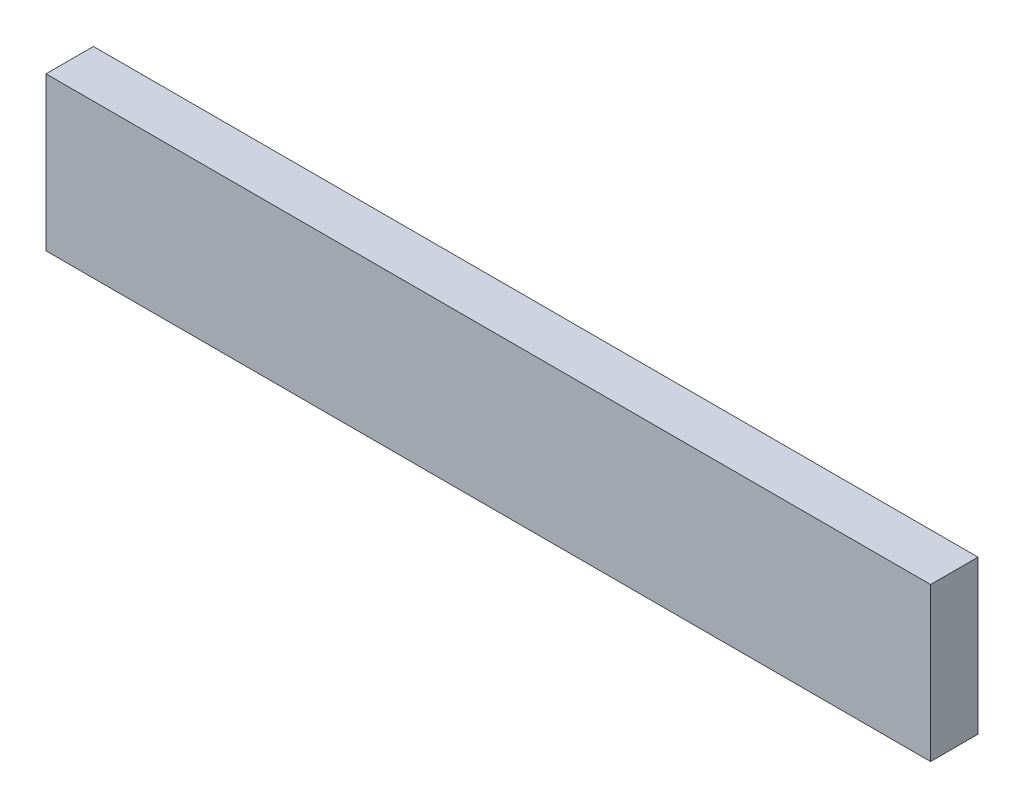
SolidWorks part; units mm, degrees
ref_plane "Front Plane" through (0, 0, 0) normal (0, 0, 1) x (1, 0, 0)
ref_plane "Top Plane" through (0, 0, 0) normal (0, 1, 0) x (1, 0, 0)
ref_plane "Right Plane" through (0, 0, 0) normal (1, 0, 0) x (0, 0, -1)
sketch "Sketch1" plane through (0, 0, 0) normal (0, 0, 1) x (1, 0, 0)
  line L1 (-27.9798, -4.85) -> (27.9798, -4.85)
  line L2 (-27.9798, -4.85) -> (-27.9798, 4.85)
  line L3 (-27.9798, 4.85) -> (27.9798, 4.85)
  line L4 (27.9798, -4.85) -> (27.9798, 4.85)
  line L5 (-27.9798, -4.85) -> (27.9798, 4.85) construction
  line L6 (-27.9798, 4.85) -> (27.9798, -4.85) construction
  point P0 (0, 0)
  dimension "D1" = 55.9596
  dimension "D2" = 9.7
extrude "Boss-Extrude1" add sketch "Sketch1" along normal blind 3
